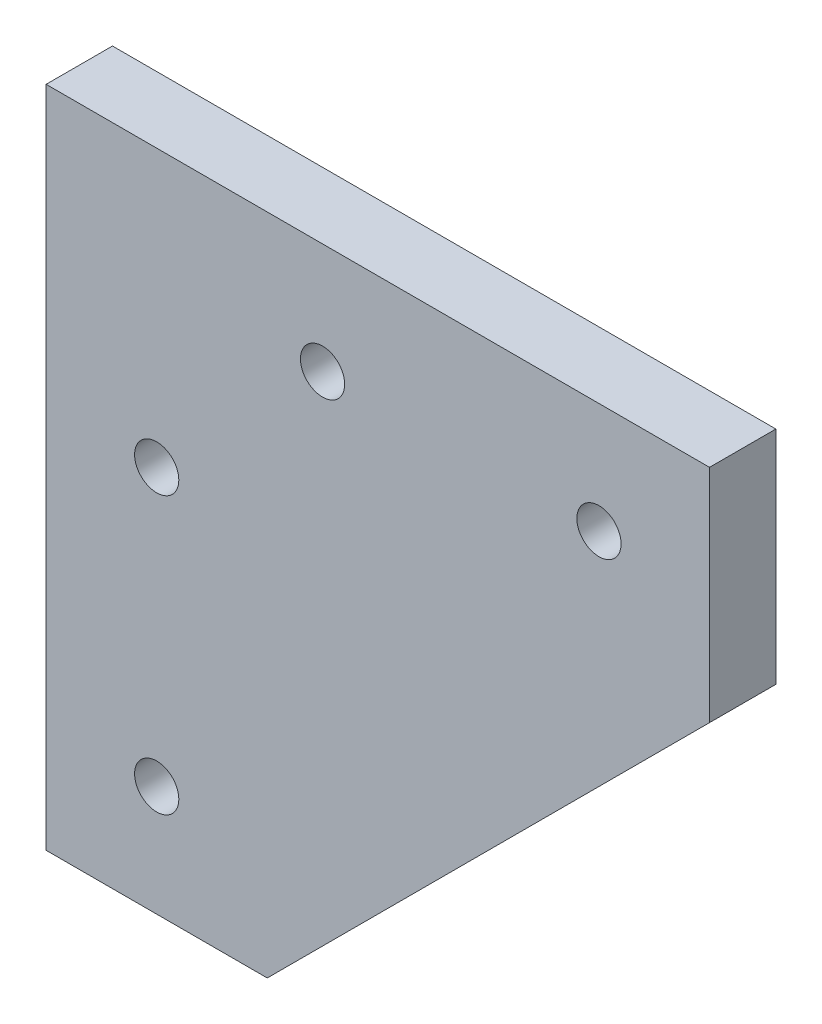
SolidWorks part; units mm, degrees
ref_plane "Front Plane" through (0, 0, 0) normal (0, 0, 1) x (1, 0, 0)
ref_plane "Top Plane" through (0, 0, 0) normal (0, 1, 0) x (1, 0, 0)
ref_plane "Right Plane" through (0, 0, 0) normal (1, 0, 0) x (0, 0, -1)
sketch "Sketch1" plane through (0, 0, 0) normal (0, 0, 1) x (1, 0, 0)
  line L0 (20, -60) -> (60, -20)
  line L1 (0, 0) -> (60, 0)
  line L2 (0, 0) -> (0, -60)
  line L3 (0, -60) -> (20, -60)
  line L4 (60, 0) -> (60, -20)
  line L5 (10, -60) -> (10, -50) construction
  line L6 (10, -50) -> (10, -25) construction
  line L7 (10, -25) -> (10, -10) construction
  line L8 (10, -10) -> (25, -10) construction
  line L9 (25, -10) -> (50, -10) construction
  line L10 (50, -10) -> (60, -10) construction
  circle A0 centre (50, -10) radius 2
  circle A1 centre (25, -10) radius 2
  circle A2 centre (10, -50) radius 2
  circle A3 centre (10, -25) radius 2
  dimension "D3" = 4
  dimension "D1" = 60
  dimension "D2" = 20
  dimension "D4" = 10
  dimension "D5" = 25
  dimension "D6" = 25
  dimension "D7" = 10
extrude "Boss-Extrude1" add sketch "Sketch1" along normal blind 6
